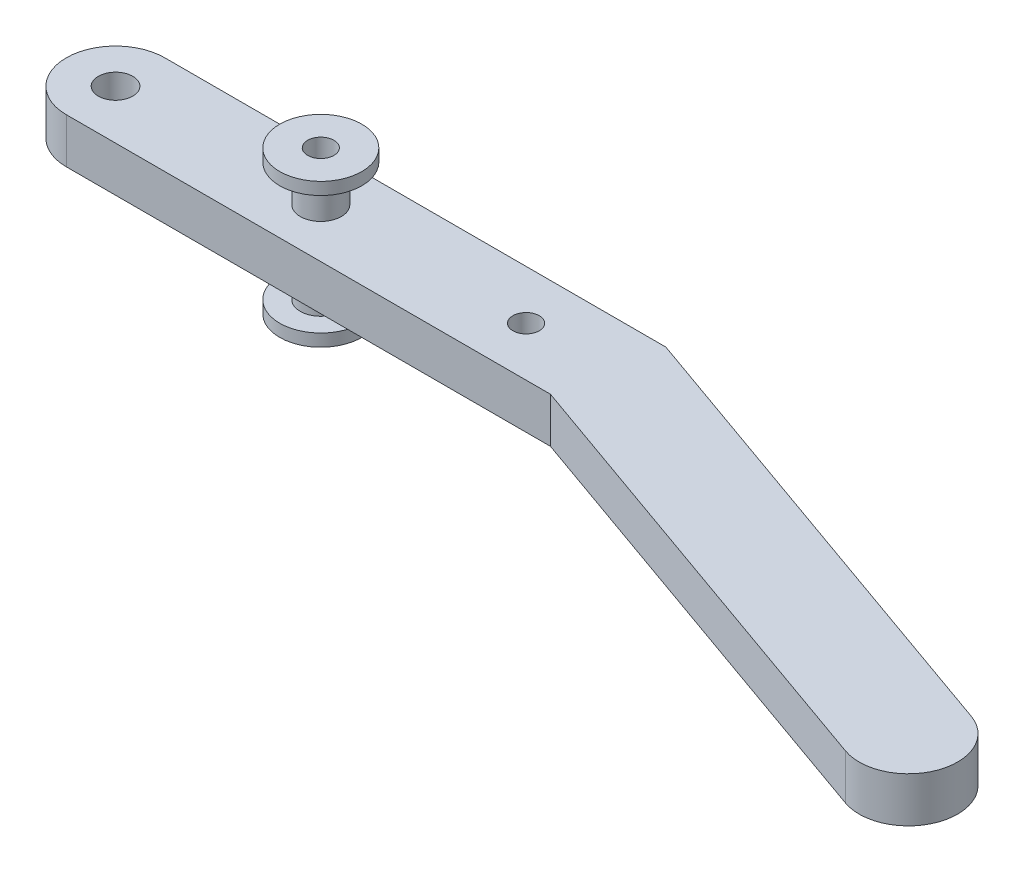
SolidWorks part; units mm, degrees
material "ﾎﾟﾘｵｷｼﾒﾁﾚﾝ(POM)ｱｾﾀｰﾙ共重合体"
ref_plane "正面" through (0, 0, 0) normal (0, 0, 1) x (1, 0, 0)
ref_plane "平面" through (0, 0, 0) normal (0, 1, 0) x (1, 0, 0)
ref_plane "右側面" through (0, 0, 0) normal (1, 0, 0) x (0, 0, -1)
sketch "ｽｹｯﾁ1" plane through (0, 0, 0) normal (0, 1, 0) x (1, 0, 0)
  line L0 (0, 0) -> (60, 0) construction
  line L1 (0, 6) -> (61.0294, 6)
  line L2 (0, -6) -> (58.9706, -6)
  line L3 (60, 0) -> (116.5685, -20) construction
  line L4 (61.0294, 6) -> (118.5685, -14.3431)
  line L5 (58.9706, -6) -> (114.5685, -25.6569)
  arc A0 (0, 6) -> (0, -6) centre (0, 0) ccw
  circle A2 centre (0, 0) radius 2.1
  arc A4 (114.5685, -25.6569) -> (118.5685, -14.3431) centre (116.5685, -20) ccw
  circle A5 centre (50, 0) radius 1.6
  circle A6 centre (25, 0) radius 1.6
  dimension "D1" = 4.2
  dimension "D2" = 6
  dimension "D6" = 3.2
  dimension "D8" = 3.2
  dimension "D3" = 60
  dimension "D4" = 60
  dimension "D5" = 20
  dimension "D7" = 50
  dimension "D9" = 25
extrude "ﾎﾞｽ - 押し出し1" add sketch "ｽｹｯﾁ1" along normal blind 5.5
sketch "ｽｹｯﾁ2" plane through (0, 5.5, 0) normal (0, 1, 0) x (1, 0, 0)
  circle A0 centre (25, 0) radius 2.5
  circle A1 centre (25, 0) radius 1.6
  circle A2 centre (25, 0) radius 1.6 construction
  dimension "D1" = 5
extrude "ﾎﾞｽ - 押し出し2" add sketch "ｽｹｯﾁ2" along normal blind 4.5 separate body
sketch "ｽｹｯﾁ3" plane through (0, 10, 0) normal (0, 1, 0) x (1, 0, 0)
  circle A0 centre (25, 0) radius 1.6 construction
  circle A1 centre (25, 0) radius 1.6
  circle A2 centre (25, 0) radius 5
  dimension "D1" = 10
extrude "ﾎﾞｽ - 押し出し4" add sketch "ｽｹｯﾁ3" along normal blind 1.5
ref_plane "平面1" through (0, 2.75, 0) normal (0, 1, 0) x (1, 0, 0)
mirror "ﾐﾗｰ1" about plane through (0, 2.75, 0) normal (0, 1, 0) of bodies 104
